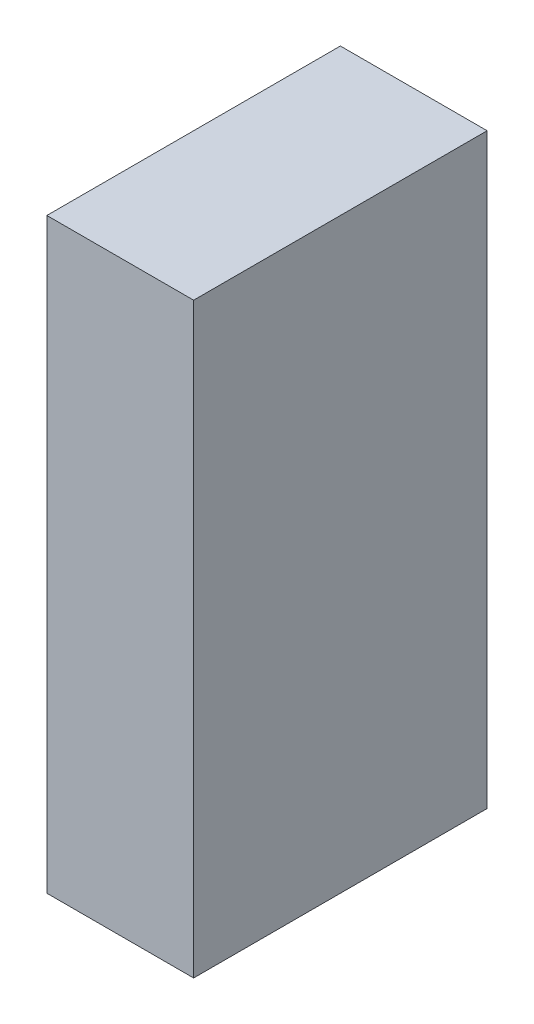
SolidWorks part; units mm, degrees
ref_plane "Front Plane" through (0, 0, 0) normal (0, 0, 1) x (1, 0, 0)
ref_plane "Top Plane" through (0, 0, 0) normal (0, 1, 0) x (1, 0, 0)
ref_plane "Right Plane" through (0, 0, 0) normal (1, 0, 0) x (0, 0, -1)
sketch "Sketch1" plane through (0, 0, 0) normal (0, 1, 0) x (1, 0, 0)
  line L1 (-68.9701, 14.7344) -> (-43.5701, 14.7344)
  line L2 (-68.9701, 14.7344) -> (-68.9701, -36.0656)
  line L3 (-68.9701, -36.0656) -> (-43.5701, -36.0656)
  line L4 (-43.5701, 14.7344) -> (-43.5701, -36.0656)
extrude "Boss-Extrude1" add sketch "Sketch1" against normal blind 101.6
